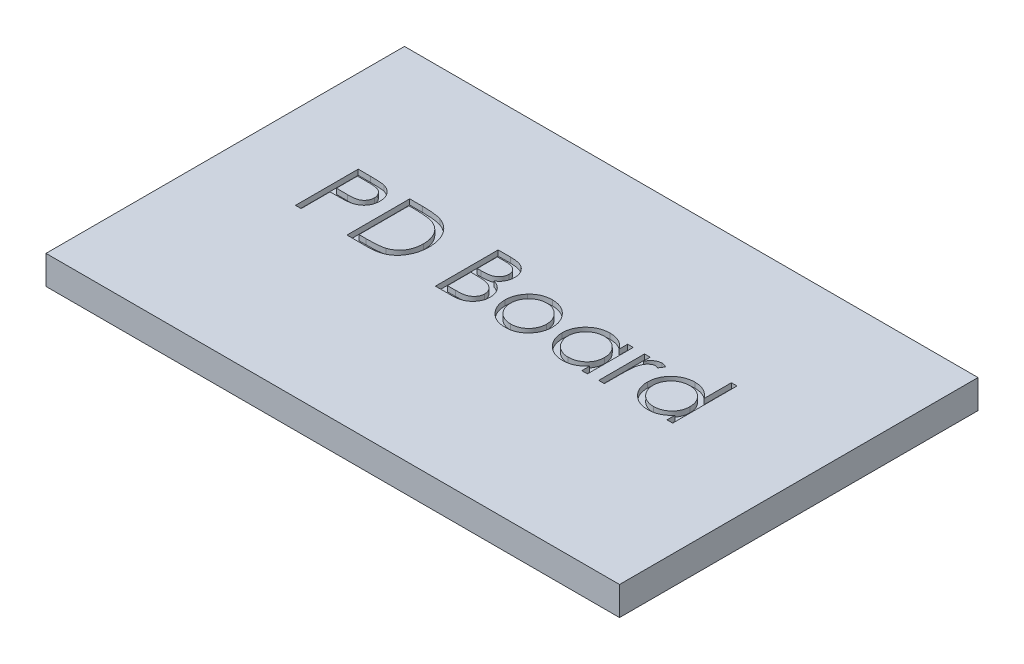
SolidWorks part; units mm, degrees
ref_plane "Front Plane" through (0, 0, 0) normal (0, 0, 1) x (1, 0, 0)
ref_plane "Top Plane" through (0, 0, 0) normal (0, 1, 0) x (1, 0, 0)
ref_plane "Right Plane" through (0, 0, 0) normal (1, 0, 0) x (0, 0, -1)
sketch "Sketch1" plane through (0, 0, 0) normal (0, 1, 0) x (1, 0, 0)
  line L1 (-16, -10) -> (16, -10)
  line L2 (-16, -10) -> (-16, 10)
  line L3 (-16, 10) -> (16, 10)
  line L4 (16, -10) -> (16, 10)
  line L5 (-16, -10) -> (16, 10) construction
  line L6 (-16, 10) -> (16, -10) construction
  point P0 (0, 0)
  dimension "D1" = 32
  dimension "D2" = 20
extrude "Boss-Extrude1" add sketch "Sketch1" along normal blind 1.6
sketch "Sketch2" plane through (0, 1.6, 0) normal (0, 1, 0) x (1, 0, 0)
  text T0 "PD Board"
extrude "Cut-Extrude1" cut sketch "Sketch2" against normal blind 0.3
